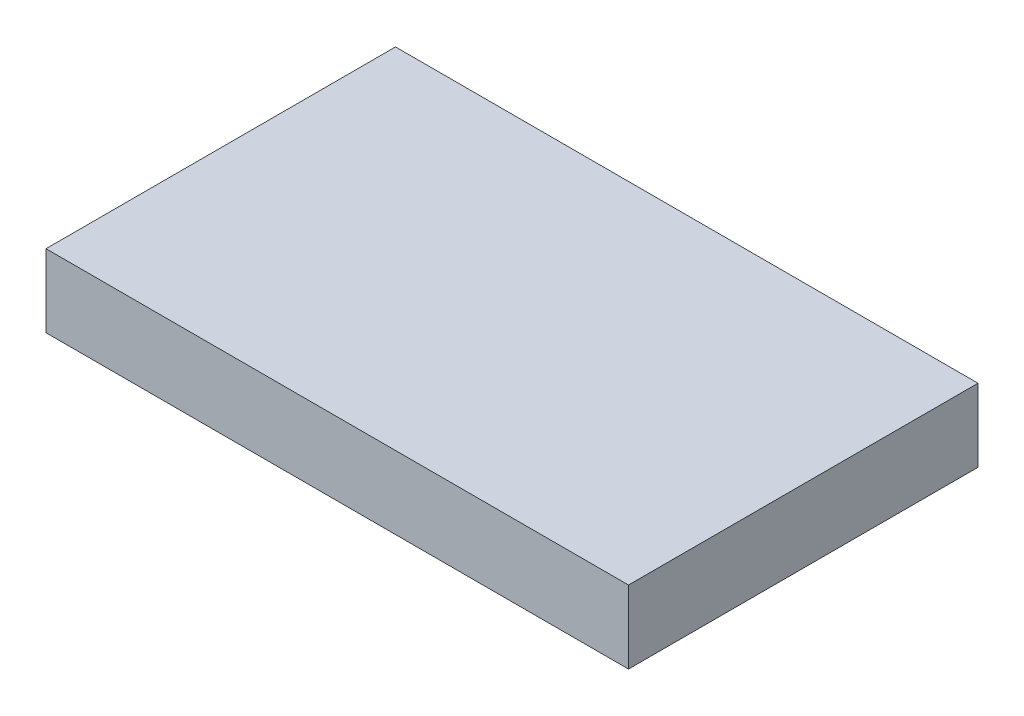
SolidWorks part; units mm, degrees
ref_plane "前视基准面" through (0, 0, 0) normal (0, 0, 1) x (1, 0, 0)
ref_plane "上视基准面" through (0, 0, 0) normal (0, 1, 0) x (1, 0, 0)
ref_plane "右视基准面" through (0, 0, 0) normal (1, 0, 0) x (0, 0, -1)
other "Configuration Table"
sketch "草图1" plane through (0, 0, 0) normal (0, 1, 0) x (1, 0, 0)
  line L1 (-100, -60) -> (100, -60)
  line L2 (-100, -60) -> (-100, 60)
  line L3 (-100, 60) -> (100, 60)
  line L4 (100, -60) -> (100, 60)
extrude "凸台-拉伸1" add sketch "草图1" against normal blind 25
sketch "草图2" plane through (0, 0, 0) normal (0, 1, 0) x (1, 0, 0)
  circle A0 centre (0, 0) radius 18
sketch "草图3" plane through (0, 0, 0) normal (0, 1, 0) x (1, 0, 0)
  circle A0 centre (-70, -40) radius 5
